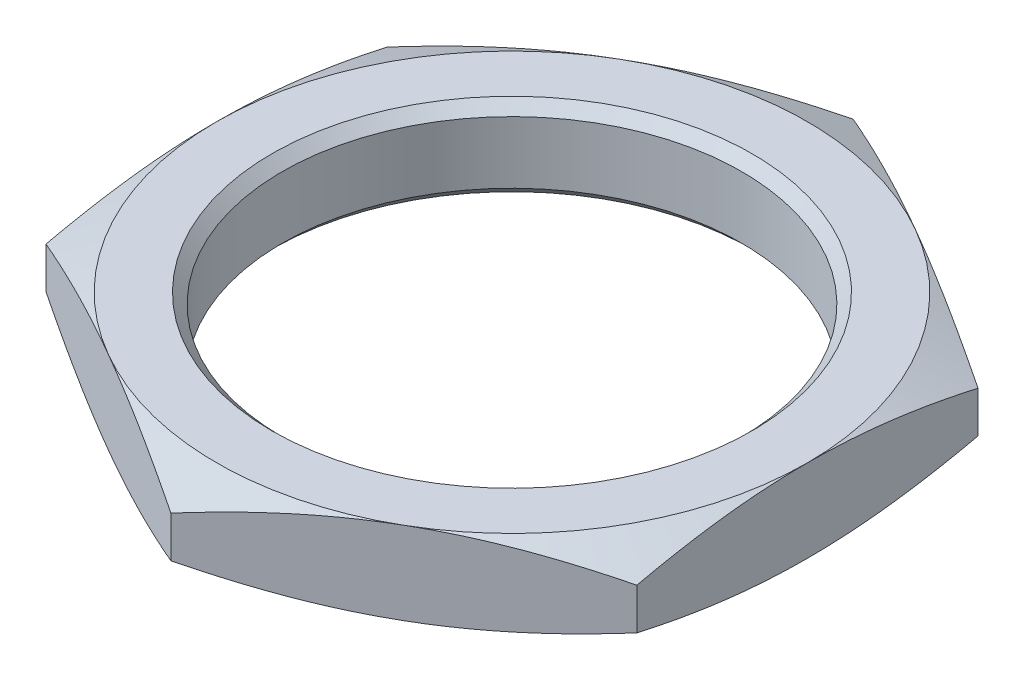
SolidWorks part; units mm, degrees
ref_plane "Front Plane" through (0, 0, 0) normal (0, 0, 1) x (1, 0, 0)
ref_plane "Top Plane" through (0, 0, 0) normal (0, 1, 0) x (1, 0, 0)
ref_plane "Right Plane" through (0, 0, 0) normal (1, 0, 0) x (0, 0, -1)
sketch "Sketch1" plane through (0, 0, 0) normal (0, 1, 0) x (1, 0, 0)
  line L1 (0, 8.25) -> (-7.1447, 4.125)
  line L2 (-7.1447, 4.125) -> (-7.1447, -4.125)
  line L3 (-7.1447, -4.125) -> (0, -8.25)
  line L4 (0, -8.25) -> (7.1447, -4.125)
  line L5 (7.1447, -4.125) -> (7.1447, 4.125)
  line L6 (7.1447, 4.125) -> (0, 8.25)
  circle A0 centre (0, 0) radius 5.5562
  circle A1 centre (0, 0) radius 8.25 construction
  circle A2 centre (0, 0) radius 7.1447 construction
  dimension "D1" = 11.1125
  dimension "D2" = 16.5
extrude "Boss-Extrude1" add sketch "Sketch1" along normal mid plane 2
sketch "Sketch4" plane through (0, 0, 0) normal (0, 0, 1) x (1, 0, 0)
  line L0 (0, 1) -> (0, -1) construction
  line L1 (0, 0) -> (-7.1447, 0) construction
  line L2 (-7.1447, 1) -> (-7.1447, -1) construction
  line L3 (-7.1447, 1) -> (-8.25, 0.5)
  line L4 (-8.6447, 2) -> (-7.1447, 2)
  line L5 (-8.6447, 2) -> (-8.6447, 0.5)
  line L6 (-8.6447, 0.5) -> (-8.25, 0.5)
  line L7 (-7.1447, 2) -> (-7.1447, 1)
  line L8 (-7.1447, -2) -> (-7.1447, -1)
  line L9 (-8.6447, -0.5) -> (-8.25, -0.5)
  line L10 (-8.6447, -2) -> (-8.6447, -0.5)
  line L11 (-8.6447, -2) -> (-7.1447, -2)
  line L12 (-7.1447, -1) -> (-8.25, -0.5)
  line L13 (-7.1447, 1) -> (0, 1) construction
  point P27 (-8.25, 0)
  dimension "D1" = 0.5
  dimension "D2" = 1.5
revolve "Cut-Revolve1" cut sketch "Sketch4" angle 360 about L0
chamfer "Chamfer1" distance 0.25 2 edges at (0, -1, 5.5562) (0, 1, 5.5562)
